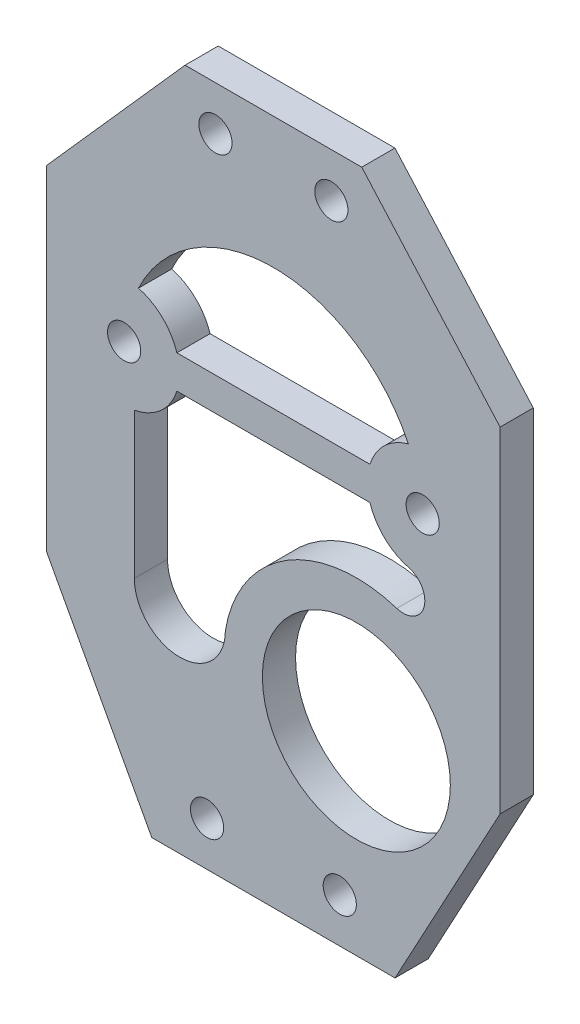
SolidWorks part; units mm, degrees
ref_plane "정면" through (0, 0, 0) normal (0, 0, 1) x (1, 0, 0)
ref_plane "윗면" through (0, 0, 0) normal (0, 1, 0) x (1, 0, 0)
ref_plane "우측면" through (0, 0, 0) normal (1, 0, 0) x (0, 0, -1)
sketch "스케치1" plane through (0, 0, 0) normal (0, 0, 1) x (1, 0, 0)
  line L0 (11, 0) -> (-11, 0)
  line L2 (0, 0) -> (0, 62) construction
  line L5 (-11, 0) -> (-20.5, 17.5997)
  line L6 (-20.5, 17.5997) -> (-20.5, 47.8997)
  line L7 (-20.5, 47.8997) -> (-7.9898, 62)
  line L8 (-7.9898, 62) -> (7.9898, 62)
  line L9 (11, 0) -> (20.5, 17.5997)
  line L10 (20.5, 17.5997) -> (20.5, 47.8997)
  line L11 (20.5, 47.8997) -> (7.9898, 62)
  line L12 (7.5, 17.5997) -> (20.5, 17.5997) construction
  line L13 (-12.5787, 32.6853) -> (-12.5787, 19.5051)
  line L14 (8.7303, 36.0997) -> (-8.7303, 36.0997)
  line L15 (8.7303, 36.0997) -> (8.7303, 39.0997)
  line L16 (8.7303, 39.0997) -> (-8.7303, 39.0997)
  line L17 (-8.7303, 36.0997) -> (-8.7303, 39.0997)
  line L18 (8.7303, 36.0997) -> (-8.7303, 39.0997) construction
  line L19 (8.7303, 39.0997) -> (-8.7303, 36.0997) construction
  circle A0 centre (-5.2398, 58) radius 1.5
  circle A1 centre (-6, 4) radius 1.5
  circle A2 centre (-13.5, 37.5997) radius 1.5
  circle A3 centre (6, 4) radius 1.5
  circle A4 centre (13.5, 37.5997) radius 1.5
  circle A5 centre (5.2398, 58) radius 1.5
  circle A6 centre (7.5, 17.5997) radius 8.5
  circle A7 centre (13.5, 37.5997) radius 5 construction
  circle A9 centre (-13.5, 37.5997) radius 5 construction
  arc A10 (-12.2023, 42.4284) -> (12.2023, 42.4284) centre (0, 36.6532) cw
  arc A11 (-12.2023, 42.4284) -> (-8.7303, 39.0997) centre (-13.5, 37.5997) cw
  arc A12 (8.7303, 39.0997) -> (12.2023, 42.4284) centre (13.5, 37.5997) cw
  arc A13 (8.7303, 36.0997) -> (12.2023, 32.771) centre (13.5, 37.5997) ccw
  arc A14 (-8.7303, 36.0997) -> (-12.5787, 32.6853) centre (-13.5, 37.5997) cw
  circle A15 centre (7.5, 17.5997) radius 12 construction
  arc A16 (11.1567, 29.029) -> (12.2023, 32.771) centre (11.7491, 30.8806) ccw
  arc A17 (-12.5787, 19.5051) -> (-4.3478, 19.5051) centre (-8.4632, 19.5051) ccw
  arc A18 (11.1567, 29.029) -> (-4.3478, 19.5051) centre (7.5, 17.5997) ccw
  point P35 (0, 50.1532)
  point P36 (0, 37.5997)
  dimension "D2" = 3
  dimension "D3" = 3
  dimension "D9" = 3
  dimension "D17" = 17
  dimension "D20" = 3.5
  dimension "D21" = 13.5
  dimension "D4" = 6
  dimension "D5" = 4
  dimension "D6" = 11
  dimension "D7" = 20
  dimension "D8" = 30.3
  dimension "D10" = 10.3
  dimension "D11" = 2.75
  dimension "D12" = 4
  dimension "D13" = 18.85
  dimension "D14" = 7
  dimension "D15" = 20.5
  dimension "D16" = 62
  dimension "D18" = 13
  dimension "D22" = 3
  dimension "D19" = 3.5
  dimension "D23" = 3.5
extrude "보스-돌출1" add sketch "스케치1" along normal blind 3 contours L10 L11 L8 L7 L6 L5 L0 L9 A6 A4 A0 A1 A2 A3 A5 A16 A18 A17 L13 A14 L17 A11 A10 A12 L15 A13 | L17 L14 L15 L16
